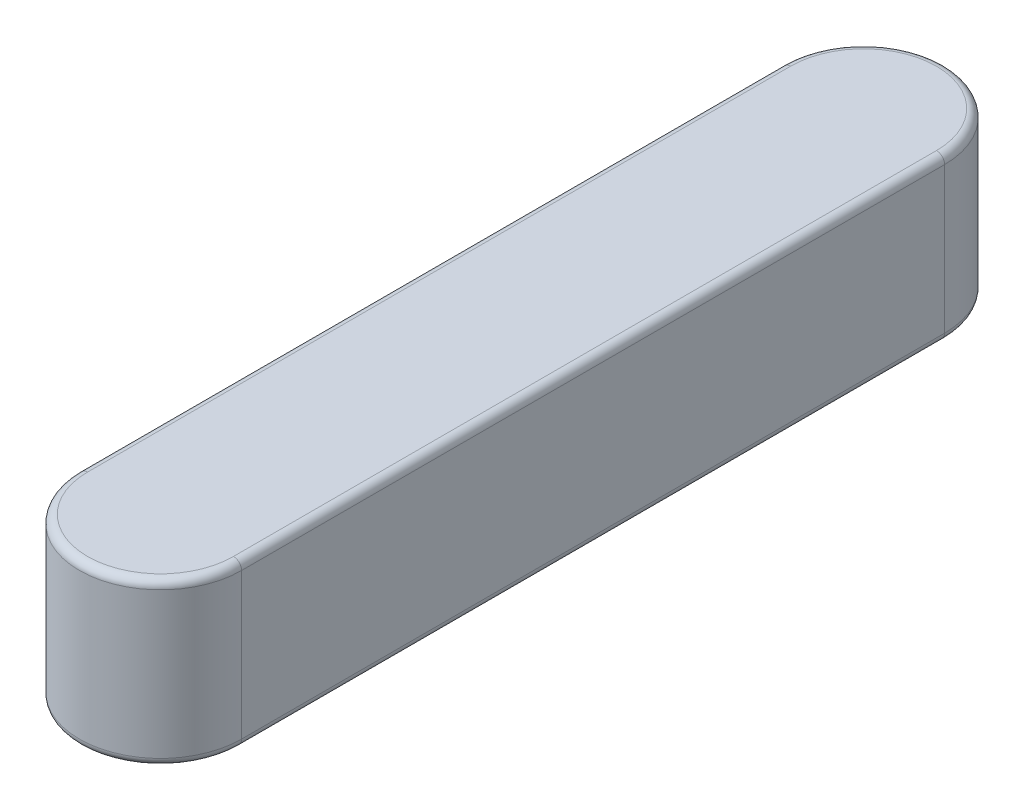
SolidWorks part; units mm, degrees
material "AISI 1045 Steel, cold drawn"
ref_plane "Front Plane" through (0, 0, 0) normal (0, 0, 1) x (1, 0, 0)
ref_plane "Top Plane" through (0, 0, 0) normal (0, 1, 0) x (1, 0, 0)
ref_plane "Right Plane" through (0, 0, 0) normal (1, 0, 0) x (0, 0, -1)
sketch "Sketch2" plane through (0, 0, 0) normal (1, 0, 0) x (0, 0, -1)
  line L0 (0, 2.3813) -> (0, -2.3813) construction
  line L1 (-12.7, -2.3813) -> (12.7, -2.3813)
  line L2 (-12.7, -2.3813) -> (-12.7, 2.3813)
  line L3 (-12.7, 2.3813) -> (12.7, 2.3813)
  line L4 (12.7, -2.3813) -> (12.7, 2.3813)
  line L5 (-12.7, -2.3813) -> (12.7, 2.3813) construction
  line L6 (-12.7, 2.3813) -> (12.7, -2.3813) construction
  line L7 (-12.7, 0) -> (12.7, 0) construction
  point P0 (0, 0)
  dimension "Length" = 25.4
  dimension "Height" = 4.7625
sketch "Sketch3" plane through (0, 0, 0) normal (0, 1, 0) x (1, 0, 0)
  line L0 (0, -12.7) -> (0, 12.7) construction
  line L5 (-2.3813, -12.7) -> (2.3812, -12.7)
  line L6 (-2.3813, -12.7) -> (-2.3813, 12.7)
  line L7 (-2.3813, 12.7) -> (2.3812, 12.7)
  line L8 (2.3812, -12.7) -> (2.3812, 12.7)
  line L9 (-2.3813, -12.7) -> (2.3812, 12.7) construction
  line L10 (-2.3813, 12.7) -> (2.3812, -12.7) construction
  point P0 (0, 0)
  dimension "Width" = 4.7625
sketch "Sketch4" plane through (0, 0, 0) normal (0, 1, 0) x (1, 0, 0)
  line L0 (0, -12.7) -> (0, 12.7) construction
  line L1 (-2.3812, 10.3187) -> (2.3812, 10.3187) construction
  line L2 (-2.3812, 10.3187) -> (-2.3813, -10.3187)
  line L3 (-2.3813, -10.3187) -> (2.3813, -10.3187) construction
  line L4 (2.3812, 10.3187) -> (2.3813, -10.3187)
  line L5 (2.3812, -12.7) -> (2.3812, 12.7) construction
  arc A0 (-2.3813, -10.3187) -> (2.3813, -10.3187) centre (0, -10.3187) ccw
  arc A1 (-2.3812, 10.3187) -> (2.3812, 10.3187) centre (0, 10.3187) cw
  point P4 (0, 10.3187)
  point P10 (0, 12.7)
  point P11 (0, -12.7)
extrude "Boss-Extrude1" add sketch "Sketch4" against normal up to vertex (2.3813 mm away) from vertex at 2.3813 starting at point (0, 2.3813, 0)
fillet "Fillet1" radius 0.2381 8 edges at (-2.3813, -2.3813, 0) (0, -2.3813, 12.7) (2.3813, -2.3813, 0) (0, -2.3813, -12.7) (2.3813, 2.3813, 0) (0, 2.3813, 12.7) (-2.3813, 2.3813, 0) (0, 2.3813, -12.7)
equation "\"D1@Fillet1\"=.05*\"Height@Sketch2\""
